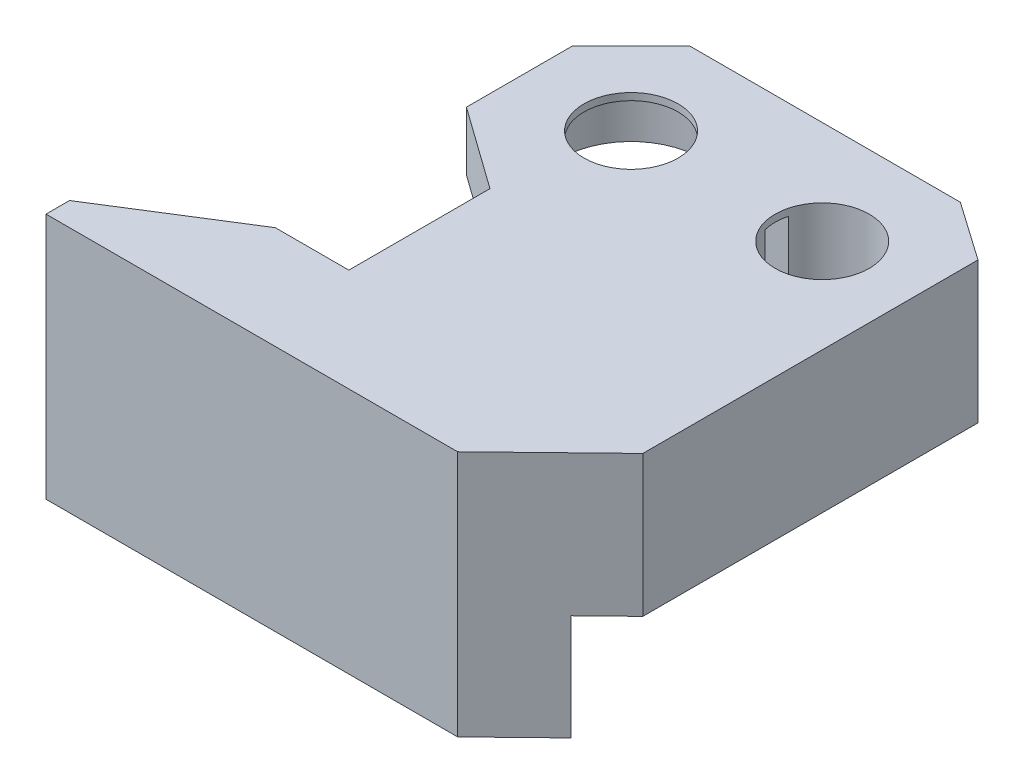
SolidWorks part; units mm, degrees
ref_plane "Front Plane" through (0, 0, 0) normal (0, 0, 1) x (1, 0, 0)
ref_plane "Top Plane" through (0, 0, 0) normal (0, 1, 0) x (1, 0, 0)
ref_plane "Right Plane" through (0, 0, 0) normal (1, 0, 0) x (0, 0, -1)
sketch "Sketch1" plane through (0, 0, 0) normal (0, 1, 0) x (1, 0, 0)
  line L0 (0, 0) -> (16.25, 0) construction
  line L5 (-3.75, 8.75) -> (19.25, 8.75)
  line L6 (19.25, 8.75) -> (24.25, 5.25)
  line L7 (24.25, 5.25) -> (24.25, -23.25)
  line L8 (24.25, -23.25) -> (16.25, -31)
  line L9 (16.25, -31) -> (-18.75, -31)
  line L10 (-18.75, -31) -> (-18.75, -29)
  line L11 (-18.75, -29) -> (-8, -22.25)
  line L12 (-8, -22.25) -> (-1.75, -22.25)
  line L13 (-1.75, -22.25) -> (-1.75, -10.25)
  line L14 (-1.75, -10.25) -> (-8.75, -5.25)
  line L15 (-8.75, -5.25) -> (-8.75, 3.75)
  line L16 (-8.75, 3.75) -> (-3.75, 8.75)
  line L17 (16.25, 0) -> (24.25, 0) construction
  circle A0 centre (0, 0) radius 4
  circle A1 centre (16.25, 0) radius 4
  point P0 (0, 0)
  point P8 (-1.75, -8.6872)
  point P20 (-8, -18.783)
  dimension "D2" = 8
  dimension "D3" = 8
  dimension "D1" = 16.25
  dimension "D4" = 23
  dimension "D5" = 5
  dimension "D6" = 3.5
  dimension "D7" = 28.5
  dimension "D8" = 8
  dimension "D9" = 8.75
  dimension "D10" = 5
  dimension "D11" = 5
  dimension "D12" = 7
  dimension "D13" = 5
  dimension "D14" = 9
  dimension "D15" = 8
  dimension "D16" = 7.75
  dimension "D17" = 35
  dimension "D18" = 6.25
  dimension "D19" = 6.75
  dimension "D20" = 2
extrude "Boss-Extrude1" add sketch "Sketch1" along normal blind 5
sketch "Sketch2" plane through (0, 0, 0) normal (0, -1, 0) x (1, 0, 0)
  line L0 (24.25, 23.25) -> (24.25, -5.25)
  line L1 (24.25, -5.25) -> (20.75, -5.25)
  line L2 (20.75, -5.25) -> (20.75, 22.25)
  line L3 (20.75, 22.25) -> (-8, 22.25)
  line L4 (-8, 22.25) -> (-14.3704, 26.25)
  line L5 (-8, 22.25) -> (-18.75, 29) construction
  line L6 (-14.3704, 26.25) -> (21.1532, 26.25)
  line L7 (16.25, 31) -> (24.25, 23.25) construction
  line L8 (21.1532, 26.25) -> (24.25, 23.25)
  dimension "D1" = 3.5
  dimension "D2" = 4
extrude "Boss-Extrude2" add sketch "Sketch2" along normal blind 7
sketch "Sketch3" plane through (0, 0, 0) normal (0, -1, 0) x (1, 0, 0)
  line L5 (-14.3704, 26.25) -> (21.1532, 26.25)
  line L6 (21.1532, 26.25) -> (16.25, 31)
  line L7 (16.25, 31) -> (-18.75, 31)
  line L8 (-18.75, 31) -> (-18.75, 29)
  line L9 (-18.75, 29) -> (-14.3704, 26.25)
  line L10 (-14.3704, 26.25) -> (21.1532, 26.25)
  line L11 (21.1532, 26.25) -> (16.25, 31)
  line L12 (16.25, 31) -> (-18.75, 31)
  line L13 (-18.75, 31) -> (-18.75, 29)
  line L14 (-18.75, 29) -> (-14.3704, 26.25)
  dimension "D1" = 0
extrude "Boss-Extrude3" add sketch "Sketch3" along normal blind 16
sketch "Sketch6" plane through (0, 0, 0) normal (0, -1, 0) x (1, 0, 0)
  circle A0 centre (16.25, 0) radius 7
  circle A1 centre (16.25, 0) radius 4
  dimension "D1" = 14
extrude "Boss-Extrude4" add sketch "Sketch6" along normal blind 2.5
sketch "Sketch4" plane through (0, 0, 0) normal (0, -1, 0) x (1, 0, 0)
  line L0 (0, 0) -> (12.25, 0) construction
  line L1 (5.8838, -1) -> (12.377, -1)
  line L2 (5.8838, 1) -> (12.377, 1)
  line L3 (0, -1) -> (16.25, -1) construction
  line L4 (0, 1) -> (16.25, 1) construction
  line L5 (0, 0) -> (16.25, 0) construction
  arc A0 (5.8838, 1) -> (5.8838, -1) centre (0, 0) ccw
  arc A2 (12.377, 1) -> (12.377, -1) centre (16.25, 0) ccw
  dimension "D1" = 1
  dimension "D2" = 1
extrude "Cut-Extrude1" cut sketch "Sketch4" against normal blind 4.4
sketch "Sketch7" plane through (0, 4.4, 0) normal (0, -1, 0) x (1, 0, 0)
  line L2 (5.8838, -1) -> (12.377, -1)
  line L3 (12.377, 1) -> (5.8838, 1)
  line L4 (5.8838, -1) -> (12.377, -1)
  line L5 (12.377, 1) -> (5.8838, 1)
  arc A2 (5.8838, 1) -> (5.8838, -1) centre (0, 0) ccw
  arc A3 (12.377, 1) -> (12.377, -1) centre (16.25, 0) ccw
  arc A4 (5.8838, 1) -> (5.8838, -1) centre (0, 0) ccw
  arc A5 (12.377, 1) -> (12.377, -1) centre (16.25, 0) ccw
  dimension "D1" = 0
extrude "Cut-Extrude2" cut sketch "Sketch7" along normal through all
